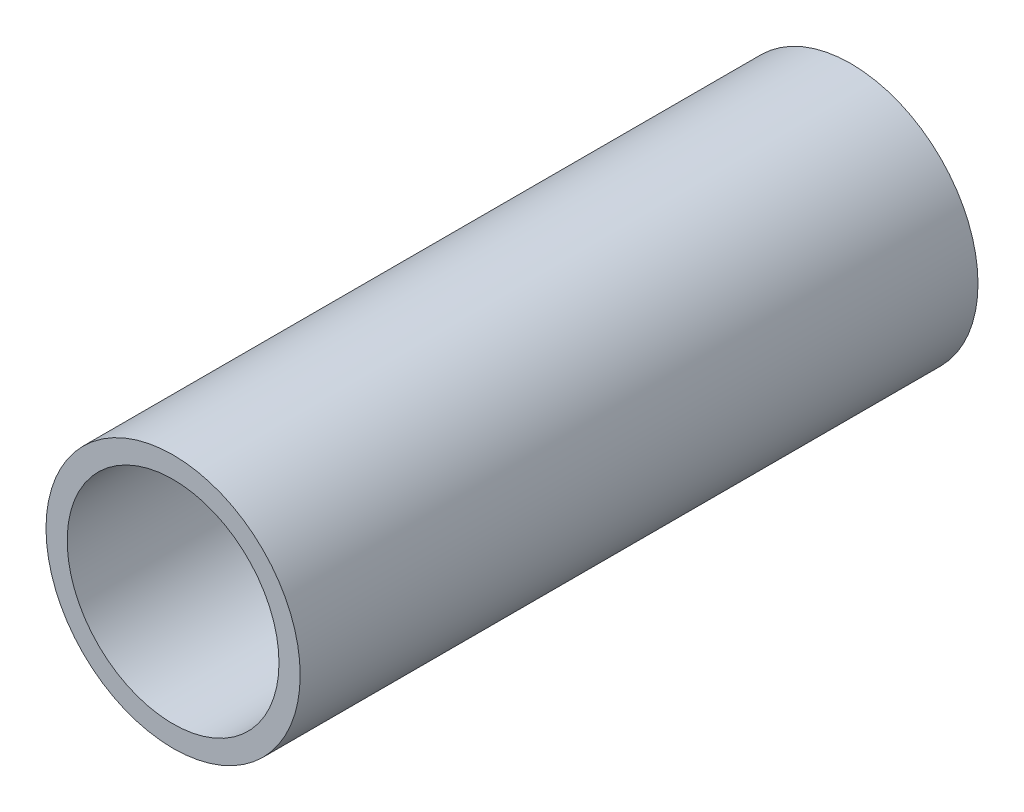
SolidWorks part; units mm, degrees
material "PVC Rigid"
ref_plane "Front Plane" through (0, 0, 0) normal (0, 0, 1) x (1, 0, 0)
ref_plane "Top Plane" through (0, 0, 0) normal (0, 1, 0) x (1, 0, 0)
ref_plane "Right Plane" through (0, 0, 0) normal (1, 0, 0) x (0, 0, -1)
sketch "Sketch1" plane through (0, 0, 0) normal (0, 0, 1) x (1, 0, 0)
  circle A0 centre (0, 0) radius 38.1
  dimension "D1" = 76.2
extrude "Extrude-Thin1" add sketch "Sketch1" along normal blind 203.2 thin thin type one direction reverse wall 6.35
